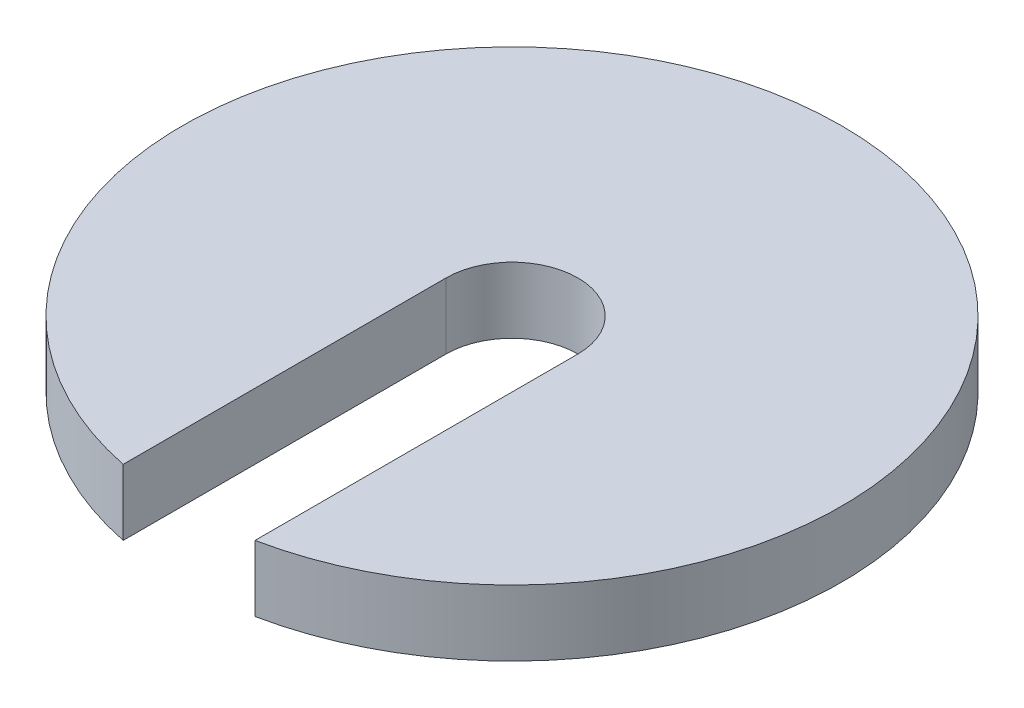
SolidWorks part; units mm, degrees
ref_plane "Front Plane" through (0, 0, 0) normal (0, 0, 1) x (1, 0, 0)
ref_plane "Top Plane" through (0, 0, 0) normal (0, 1, 0) x (1, 0, 0)
ref_plane "Right Plane" through (0, 0, 0) normal (1, 0, 0) x (0, 0, -1)
sketch "Sketch1" plane through (0, 0, 0) normal (0, 1, 0) x (1, 0, 0)
  line L0 (-30, -146.9694) -> (-30, 0)
  line L1 (30, 0) -> (30, -146.9694)
  arc A0 (30, -146.9694) -> (-30, -146.9694) centre (0, 0) ccw
  arc A1 (30, 0) -> (-30, 0) centre (0, 0) ccw
  dimension "D1" = 30
  dimension "D2" = 150
extrude "Boss-Extrude1" add sketch "Sketch1" along normal mid plane 30
sketch "Sketch2" plane through (0, 15, 0) normal (0, 1, 0) x (1, 0, 0)
  line L0 (0, -1000) -> (0, 49000) construction
  line L1 (-1000, 0) -> (49000, 0) construction
  line L2 (0, 0) -> (-75, -129.9038) construction
  line L3 (0, 0) -> (75, -129.9038) construction
  arc A0 (30, -146.9694) -> (-30, -146.9694) centre (0, 0) ccw construction
  circle A1 centre (0, 0) radius 80 construction
  dimension "D2" = 160
  dimension "D1" = 60
